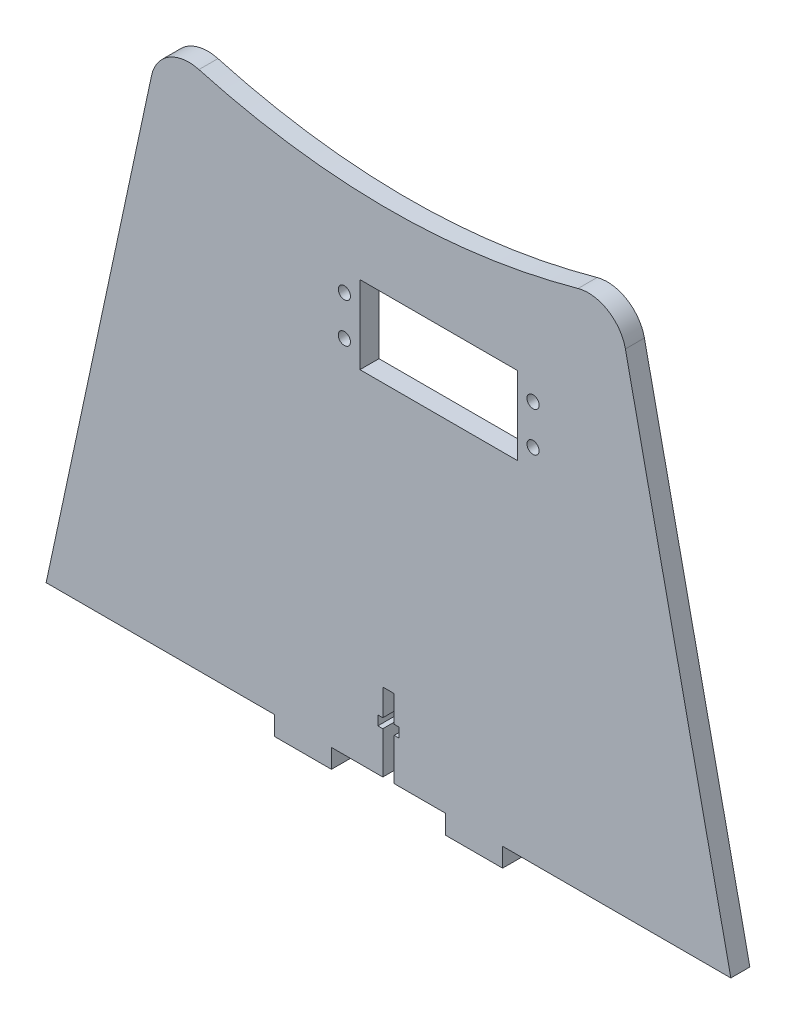
SolidWorks part; units mm, degrees
ref_plane "Front Plane" through (0, 0, 0) normal (0, 0, 1) x (1, 0, 0)
ref_plane "Top Plane" through (0, 0, 0) normal (0, 1, 0) x (1, 0, 0)
ref_plane "Right Plane" through (0, 0, 0) normal (1, 0, 0) x (0, 0, -1)
sketch "Sketch1" plane through (0, 0, 0) normal (0, 0, 1) x (1, 0, 0)
  line L0 (-27.8291, -27.0874) -> (-27.8291, -32.0874)
  line L1 (-27.8291, -32.0874) -> (-12.8291, -32.0874)
  line L2 (-12.8291, -32.0874) -> (-12.8291, -27.0874)
  line L3 (17.1709, -27.0874) -> (3.6709, -27.0874)
  line L4 (17.1709, -27.0874) -> (17.1709, -32.0874)
  line L5 (17.1709, -32.0874) -> (32.1709, -32.0874)
  line L6 (32.1709, -32.0874) -> (32.1709, -27.0874)
  line L7 (92.1709, -27.0874) -> (92.1709, 72.9126) construction
  line L8 (-87.8291, -27.0874) -> (-87.8291, 72.9126) construction
  line L9 (-5.3291, 83.1626) -> (36.0709, 83.1626)
  line L10 (-5.3291, 83.1626) -> (-5.3291, 62.6626)
  line L11 (-5.3291, 62.6626) -> (36.0709, 62.6626)
  line L12 (36.0709, 83.1626) -> (36.0709, 62.6626)
  line L13 (36.0709, 72.9126) -> (28.5709, 72.9126) construction
  line L14 (-5.3291, 72.9126) -> (2.1709, 72.9126) construction
  line L15 (92.1709, 72.9126) -> (-87.8291, 72.9126) construction
  line L16 (62.1709, -27.0874) -> (62.1709, 112.9126) construction
  line L17 (-57.8291, -27.0874) -> (-57.8291, 112.9126) construction
  line L18 (92.1709, -27.0874) -> (64.4516, 102.269)
  line L19 (-87.8291, -27.0874) -> (-60.1099, 102.269)
  line L20 (2.1709, -27.0874) -> (2.1709, 102.9126) construction
  line L21 (-87.8291, -27.0874) -> (-27.8291, -27.0874)
  line L22 (32.1709, -27.0874) -> (92.1709, -27.0874)
  line L23 (0.6709, -6.5874) -> (3.6709, -6.5874)
  line L24 (3.6709, -16.0874) -> (4.9709, -16.0874)
  line L25 (3.6709, -13.5874) -> (3.6709, -6.5874)
  line L26 (0.6709, -16.0874) -> (-0.6291, -16.0874)
  line L27 (0.6709, -6.5874) -> (0.6709, -13.5874)
  line L28 (3.6709, -27.0874) -> (3.6709, -16.0874)
  line L29 (0.6709, -27.0874) -> (0.6709, -16.0874)
  line L30 (4.9709, -16.0874) -> (4.9709, -13.5874)
  line L31 (4.9709, -13.5874) -> (3.6709, -13.5874)
  line L32 (0.6709, -13.5874) -> (-0.6291, -13.5874)
  line L33 (-0.6291, -13.5874) -> (-0.6291, -16.0874)
  line L34 (0.6709, -27.0874) -> (-12.8291, -27.0874)
  circle A0 centre (-9.4291, 78.1124) radius 1.6
  circle A1 centre (-9.4291, 67.7124) radius 1.6
  circle A2 centre (40.1709, 67.7124) radius 1.6
  circle A3 centre (40.1709, 78.1124) radius 1.6
  arc A4 (-60.1099, 102.269) -> (-47.6637, 109.8111) centre (-50.3319, 100.1737) cw
  arc A5 (64.4516, 102.269) -> (52.0054, 109.8111) centre (54.6736, 100.1737) ccw
  spline S0 degree 3 poles (52.0054, 109.8111) (35.3939, 105.2121) (2.1709, 100.6131) (-31.0522, 105.2121) (-47.6637, 109.8111) knots 0.084712 0.084712 0.084712 0.084712 0.5 0.915288 0.915288 0.915288 0.915288
  dimension "D1" = 10
extrude "Boss-Extrude1" add sketch "Sketch1" along normal blind 5
